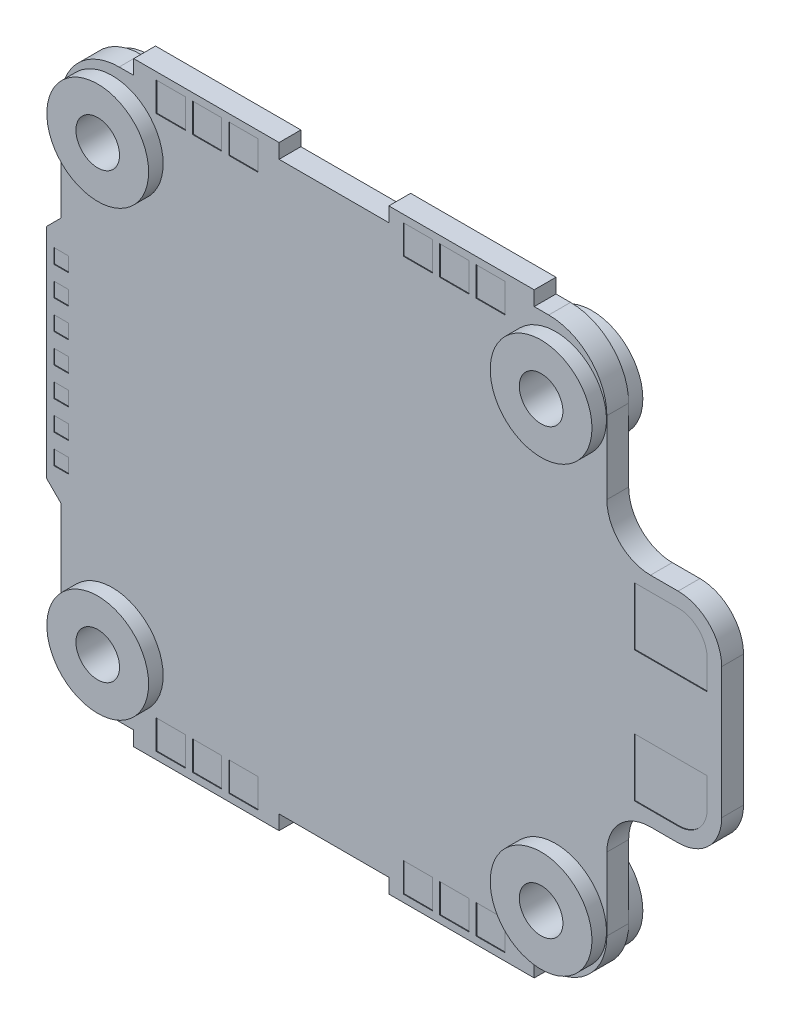
SolidWorks part; units mm, degrees
ref_plane "Alzado" through (0, 0, 0) normal (0, 0, 1) x (1, 0, 0)
ref_plane "Planta" through (0, 0, 0) normal (0, 1, 0) x (1, 0, 0)
ref_plane "Vista lateral" through (0, 0, 0) normal (1, 0, 0) x (0, 0, -1)
sketch "Croquis1" plane through (0, 0, 0) normal (0, 0, 1) x (1, 0, 0)
  line L0 (-19.6668, 13.696) -> (-19.6668, 6.696)
  line L6 (-20.6668, 5.696) -> (-20.6668, -9.304)
  line L8 (-19.6668, -10.304) -> (-19.6668, -17.304)
  line L9 (-20.6668, 5.696) -> (-19.6668, 6.696)
  line L10 (-20.6668, -9.304) -> (-19.6668, -10.304)
  line L11 (-15.6668, 17.696) -> (-14.6668, 17.696)
  line L12 (-14.6668, 17.696) -> (-14.6668, 18.696)
  line L13 (-14.6668, 18.696) -> (-4.6668, 18.696)
  line L14 (-4.6668, 18.696) -> (-4.6668, 17.696)
  line L15 (13.8832, 17.696) -> (12.8832, 17.696)
  line L16 (12.8832, 17.696) -> (12.8832, 18.696)
  line L17 (12.8832, 18.696) -> (2.8832, 18.696)
  line L18 (2.8832, 18.696) -> (2.8832, 17.696)
  line L19 (2.8832, 17.696) -> (-4.6668, 17.696)
  line L20 (-20.6668, -1.804) -> (17.8832, -1.804) construction
  line L21 (2.8832, -21.304) -> (-4.6668, -21.304)
  line L22 (2.8832, -22.304) -> (2.8832, -21.304)
  line L23 (12.8832, -22.304) -> (2.8832, -22.304)
  line L24 (12.8832, -21.304) -> (12.8832, -22.304)
  line L25 (13.8832, -21.304) -> (12.8832, -21.304)
  line L26 (-4.6668, -22.304) -> (-4.6668, -21.304)
  line L27 (-14.6668, -22.304) -> (-4.6668, -22.304)
  line L28 (-14.6668, -21.304) -> (-14.6668, -22.304)
  line L29 (-15.6668, -21.304) -> (-14.6668, -21.304)
  line L30 (17.8832, 13.696) -> (17.8832, 8.696)
  line L31 (20.8832, 5.696) -> (22.7832, 5.696)
  line L32 (25.7832, 2.696) -> (25.7832, -6.304)
  line L33 (22.7832, -9.304) -> (20.8832, -9.304)
  line L34 (17.8832, -12.304) -> (17.8832, -17.304)
  circle A0 centre (-16.1418, 13.446) radius 2.5
  circle A1 centre (14.3582, 13.446) radius 2.5
  circle A2 centre (14.3582, -17.054) radius 2.5
  circle A3 centre (-16.1418, -17.054) radius 2.5
  arc A4 (25.7832, -6.304) -> (22.7832, -9.304) centre (22.7832, -6.304) cw
  arc A5 (22.7832, 5.696) -> (25.7832, 2.696) centre (22.7832, 2.696) cw
  arc A6 (20.8832, -9.304) -> (17.8832, -12.304) centre (20.8832, -12.304) ccw
  arc A7 (17.8832, 8.696) -> (20.8832, 5.696) centre (20.8832, 8.696) ccw
  arc A8 (13.8832, -21.304) -> (17.8832, -17.304) centre (13.8832, -17.304) ccw
  arc A9 (-19.6668, -17.304) -> (-15.6668, -21.304) centre (-15.6668, -17.304) ccw
  arc A10 (13.8832, 17.696) -> (17.8832, 13.696) centre (13.8832, 13.696) cw
  arc A11 (-15.6668, 17.696) -> (-19.6668, 13.696) centre (-15.6668, 13.696) ccw
  point P48 (17.8832, -21.304)
  point P51 (-19.6668, -21.304)
  point P54 (17.8832, 17.696)
  point P57 (-19.6668, 17.696)
  dimension "D3" = 2
  dimension "D10" = 3
  dimension "D11" = 4
  dimension "D1" = 37.55
  dimension "D2" = 39
  dimension "D4" = 2
  dimension "D5" = 4.25
  dimension "D6" = 3.525
  dimension "D7" = 46.45
  dimension "D8" = 12
  dimension "D9" = 12
extrude "Saliente-Extruir1" add sketch "Croquis1" along normal blind 1.5
sketch "Croquis2" plane through (0, 0, 1.5) normal (0, 0, 1) x (1, 0, 0)
  line L0 (-18.6418, -17.054) -> (-13.6418, -17.054)
  circle A0 centre (-16.1418, -17.054) radius 2.5 construction
ref_plane "Plano1" through (0, -17.054, 0) normal (0, -1, 0) x (-1, 0, 0)
sketch "Croquis3" plane through (0, -17.054, 0) normal (0, -1, 0) x (-1, 0, 0)
  line L0 (18.6418, -1.5) -> (19.6418, -1.5)
  line L1 (19.6418, -1.5) -> (19.6418, -2.5)
  line L2 (18.6418, -1.5) -> (13.6418, -1.5) construction
  line L3 (16.1418, -1.5) -> (16.1418, -2.5) construction
  line L5 (16.1418, -2.5) -> (16.1418, 1) construction
  line L7 (19.6418, 1) -> (19.6418, 0)
  line L8 (19.6418, 0) -> (18.6418, 0)
  line L9 (18.6418, 0) -> (18.6418, -1.5)
  line L10 (19.6418, -2.5) -> (17.6418, -2.5)
  line L11 (17.6418, -2.5) -> (17.6418, 1)
  line L12 (17.6418, 1) -> (19.6418, 1)
  dimension "D1" = 1
  dimension "D2" = 1
  dimension "D3" = 1
  dimension "D4" = 1
  dimension "D5" = 3.5
  dimension "D6" = 2
revolve "Revolución1" add sketch "Croquis3" angle 360 about L5
pattern_linear "MatrizL1" count 2 spacing 30.5 along (1, 0, 0) count 2 spacing 30.5 along (0, 1, 0) of "Revolución1"
sketch "Croquis4" plane through (0, 0, 1.5) normal (0, 0, 1) x (1, 0, 0)
  line L0 (20.8832, -9.304) -> (22.7832, -9.304) construction
  line L1 (19.7832, -8.304) -> (22.7832, -8.304)
  line L2 (19.7832, -8.304) -> (19.7832, -4.304)
  line L3 (19.7832, -4.304) -> (24.7832, -4.304)
  line L4 (24.7832, -6.304) -> (24.7832, -4.304)
  line L9 (8.8832, -21.804) -> (10.8832, -21.804)
  line L10 (8.8832, -21.804) -> (8.8832, -19.804)
  line L11 (8.8832, -19.804) -> (10.8832, -19.804)
  line L12 (10.8832, -21.804) -> (10.8832, -19.804)
  line L13 (-20.1668, -8.304) -> (-19.1668, -8.304)
  line L14 (-20.1668, -8.304) -> (-20.1668, -7.304)
  line L15 (-20.1668, -7.304) -> (-19.1668, -7.304)
  line L16 (-19.1668, -8.304) -> (-19.1668, -7.304)
  line L17 (25.7832, -6.304) -> (25.7832, 2.696) construction
  line L18 (25.7832, -1.804) -> (-20.6668, -1.804) construction
  line L19 (-20.6668, 5.696) -> (-20.6668, -9.304) construction
  line L20 (12.8832, -22.304) -> (12.8832, -21.304) construction
  line L21 (2.8832, -22.304) -> (12.8832, -22.304) construction
  line L22 (6.3832, -21.804) -> (8.3832, -21.804)
  line L23 (6.3832, -21.804) -> (6.3832, -19.804)
  line L24 (6.3832, -19.804) -> (8.3832, -19.804)
  line L25 (8.3832, -21.804) -> (8.3832, -19.804)
  line L26 (3.8832, -21.804) -> (5.8832, -21.804)
  line L27 (3.8832, -21.804) -> (3.8832, -19.804)
  line L28 (3.8832, -19.804) -> (5.8832, -19.804)
  line L29 (5.8832, -21.804) -> (5.8832, -19.804)
  line L30 (-8.1168, -21.804) -> (-6.1168, -21.804)
  line L31 (-8.1168, -21.804) -> (-8.1168, -19.804)
  line L32 (-8.1168, -19.804) -> (-6.1168, -19.804)
  line L33 (-6.1168, -21.804) -> (-6.1168, -19.804)
  line L34 (-10.6168, -21.804) -> (-8.6168, -21.804)
  line L35 (-10.6168, -21.804) -> (-10.6168, -19.804)
  line L36 (-10.6168, -19.804) -> (-8.6168, -19.804)
  line L37 (-8.6168, -21.804) -> (-8.6168, -19.804)
  line L38 (-13.1168, -21.804) -> (-11.1168, -21.804)
  line L39 (-13.1168, -21.804) -> (-13.1168, -19.804)
  line L40 (-13.1168, -19.804) -> (-11.1168, -19.804)
  line L41 (-11.1168, -21.804) -> (-11.1168, -19.804)
  line L42 (-20.1668, -6.304) -> (-19.1668, -6.304)
  line L43 (-20.1668, -6.304) -> (-20.1668, -5.304)
  line L44 (-20.1668, -5.304) -> (-19.1668, -5.304)
  line L45 (-19.1668, -6.304) -> (-19.1668, -5.304)
  line L46 (-20.1668, -4.304) -> (-19.1668, -4.304)
  line L47 (-20.1668, -4.304) -> (-20.1668, -3.304)
  line L48 (-20.1668, -3.304) -> (-19.1668, -3.304)
  line L49 (-19.1668, -4.304) -> (-19.1668, -3.304)
  line L50 (-20.1668, -2.304) -> (-19.1668, -2.304)
  line L51 (-20.1668, -2.304) -> (-20.1668, -1.304)
  line L52 (-20.1668, -1.304) -> (-19.1668, -1.304)
  line L53 (-19.1668, -2.304) -> (-19.1668, -1.304)
  line L54 (-20.1668, -0.304) -> (-19.1668, -0.304)
  line L55 (-20.1668, -0.304) -> (-20.1668, 0.696)
  line L56 (-20.1668, 0.696) -> (-19.1668, 0.696)
  line L57 (-19.1668, -0.304) -> (-19.1668, 0.696)
  line L58 (-20.1668, 1.696) -> (-19.1668, 1.696)
  line L59 (-20.1668, 1.696) -> (-20.1668, 2.696)
  line L60 (-20.1668, 2.696) -> (-19.1668, 2.696)
  line L61 (-19.1668, 1.696) -> (-19.1668, 2.696)
  line L62 (-20.1668, 3.696) -> (-19.1668, 3.696)
  line L63 (-20.1668, 3.696) -> (-20.1668, 4.696)
  line L64 (-20.1668, 4.696) -> (-19.1668, 4.696)
  line L65 (-19.1668, 3.696) -> (-19.1668, 4.696)
  line L66 (-11.1168, 18.196) -> (-11.1168, 16.196)
  line L67 (-13.1168, 16.196) -> (-11.1168, 16.196)
  line L68 (-13.1168, 18.196) -> (-13.1168, 16.196)
  line L69 (-13.1168, 18.196) -> (-11.1168, 18.196)
  line L70 (-8.6168, 18.196) -> (-8.6168, 16.196)
  line L71 (-10.6168, 16.196) -> (-8.6168, 16.196)
  line L72 (-10.6168, 18.196) -> (-10.6168, 16.196)
  line L73 (-10.6168, 18.196) -> (-8.6168, 18.196)
  line L74 (-6.1168, 18.196) -> (-6.1168, 16.196)
  line L75 (-8.1168, 16.196) -> (-6.1168, 16.196)
  line L76 (-8.1168, 18.196) -> (-8.1168, 16.196)
  line L77 (-8.1168, 18.196) -> (-6.1168, 18.196)
  line L78 (5.8832, 18.196) -> (5.8832, 16.196)
  line L79 (3.8832, 16.196) -> (5.8832, 16.196)
  line L80 (3.8832, 18.196) -> (3.8832, 16.196)
  line L81 (3.8832, 18.196) -> (5.8832, 18.196)
  line L82 (8.3832, 18.196) -> (8.3832, 16.196)
  line L83 (6.3832, 16.196) -> (8.3832, 16.196)
  line L84 (6.3832, 18.196) -> (6.3832, 16.196)
  line L85 (6.3832, 18.196) -> (8.3832, 18.196)
  line L86 (10.8832, 18.196) -> (10.8832, 16.196)
  line L87 (8.8832, 16.196) -> (10.8832, 16.196)
  line L88 (8.8832, 18.196) -> (8.8832, 16.196)
  line L89 (8.8832, 18.196) -> (10.8832, 18.196)
  line L90 (24.7832, 2.696) -> (24.7832, 0.696)
  line L91 (19.7832, 0.696) -> (24.7832, 0.696)
  line L92 (19.7832, 4.696) -> (19.7832, 0.696)
  line L93 (19.7832, 4.696) -> (22.7832, 4.696)
  arc A0 (22.7832, -8.304) -> (24.7832, -6.304) centre (22.7832, -6.304) ccw
  arc A1 (22.7832, 4.696) -> (24.7832, 2.696) centre (22.7832, 2.696) cw
  point P18 (21.8332, -9.304)
  dimension "D1" = 2
  dimension "D2" = 2
  dimension "D3" = 4
  dimension "D4" = 5
  dimension "D5" = 1
  dimension "D6" = 1
  dimension "D7" = 2
  dimension "D8" = 2
  dimension "D9" = 0.5
  dimension "D12" = 0.5
  dimension "D13" = 1
  dimension "D14" = 1
  dimension "D15" = 7
  dimension "D16" = 2
  dimension "D10" = 3
  dimension "D11" = 2
extrude "Cortar-Extruir1" cut sketch "Croquis4" against normal blind 0.05
